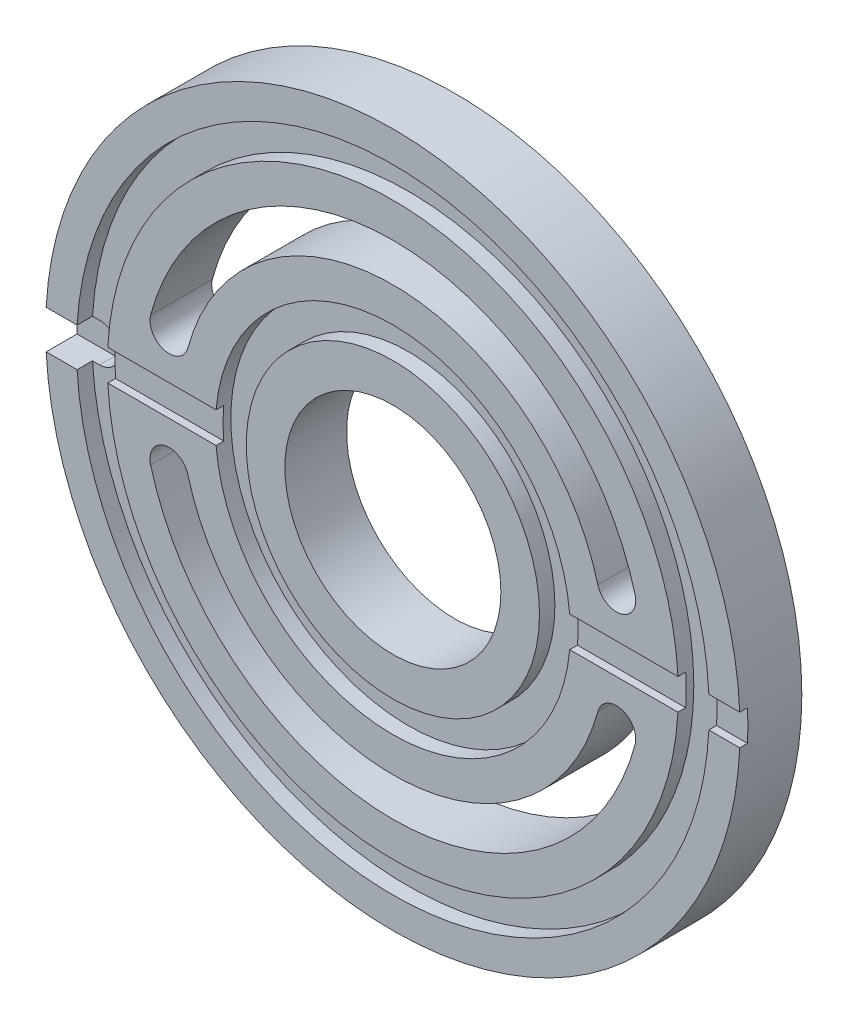
SolidWorks part; units mm, degrees
ref_plane "前视基准面" through (0, 0, 0) normal (0, 0, 1) x (1, 0, 0)
ref_plane "上视基准面" through (0, 0, 0) normal (0, 1, 0) x (1, 0, 0)
ref_plane "右视基准面" through (0, 0, 0) normal (1, 0, 0) x (0, 0, -1)
sketch "草图1" plane through (0, 0, 0) normal (0, 0, 1) x (1, 0, 0)
  circle A0 centre (0, 0) radius 45
  dimension "D1" = 90
extrude "凸台-拉伸1" add sketch "草图1" along normal blind 8
sketch "草图2" plane through (0, 0, 8) normal (0, 0, 1) x (1, 0, 0)
  circle A0 centre (0, 0) radius 14
  dimension "D1" = 28
extrude "切除-拉伸1" cut sketch "草图2" against normal through all
sketch "草图3" plane through (0, 0, 8) normal (0, 0, 1) x (1, 0, 0)
  circle A0 centre (0, 0) radius 37
  dimension "D1" = 74
extrude "切除-拉伸-薄壁1" cut sketch "草图3" against normal blind 2 thin
sketch "草图4" plane through (0, 0, 8) normal (0, 0, 1) x (1, 0, 0)
  line L0 (-45, 0) -> (-40, 0) construction
  line L1 (4.4, 0) -> (-4.4, 0) construction
  line L2 (-45, 2.5) -> (-40, 2.5)
  line L3 (-45, -2.5) -> (-40, -2.5)
  line L4 (0, -4.4) -> (0, 4.4) construction
  circle A0 centre (0, 0) radius 45 construction
  arc A1 (-45, 2.5) -> (-45, -2.5) centre (-45, 0) ccw
  arc A2 (-40, -2.5) -> (-40, 2.5) centre (-40, 0) ccw
  point P7 (-42.5, 0)
  dimension "D1" = 40
  dimension "D2" = 5
extrude "切除-拉伸2" cut sketch "草图4" against normal blind 4
sketch "草图5" plane through (0, 0, 8) normal (0, 0, 1) x (1, 0, 0)
  line L0 (0, 0) -> (46.4065, 12.4346) construction
  line L1 (4.4, 0) -> (-4.4, 0) construction
  line L2 (0, 0) -> (0, 64.943) construction
  line L3 (0, -4.4) -> (0, 4.4) construction
  arc A0 (28.9778, 7.7646) -> (-28.9778, 7.7646) centre (0, 0) ccw construction
  arc A1 (31.3926, 8.4116) -> (-31.3926, 8.4116) centre (0, 0) ccw
  arc A2 (26.563, 7.1175) -> (-26.563, 7.1175) centre (0, 0) ccw
  arc A3 (31.3926, 8.4116) -> (26.563, 7.1175) centre (28.9778, 7.7646) cw
  arc A4 (-31.3926, 8.4116) -> (-26.563, 7.1175) centre (-28.9778, 7.7646) ccw
  dimension "D2" = 30
  dimension "D1" = 15
  dimension "D3" = 2.5
  dimension "D4" = 2.5
extrude "切除-拉伸3" cut sketch "草图5" against normal through all
mirror "镜向1" about plane through (0, 0, 0) normal (0, 1, 0) of "切除-拉伸3"
sketch "草图6" plane through (0, 0, 8) normal (0, 0, 1) x (1, 0, 0)
  circle A0 centre (0, 0) radius 19
  dimension "D1" = 38
extrude "切除-拉伸-薄壁2" cut sketch "草图6" against normal blind 2 thin
sketch "草图7" plane through (0, 0, 8) normal (0, 0, 1) x (1, 0, 0)
  line L0 (-19, 0) -> (-37, 0)
  line L1 (4.4, 0) -> (-4.4, 0) construction
  line L2 (19, 0) -> (45, 0)
  circle A0 centre (0, 0) radius 19 construction
  circle A1 centre (0, 0) radius 37 construction
  arc A2 (-44.9305, -2.5) -> (-44.9305, 2.5) centre (0, 0) ccw construction
extrude "切除-拉伸-薄壁3" cut sketch "草图7" against normal blind 1 thin thin type mid plane wall 4
